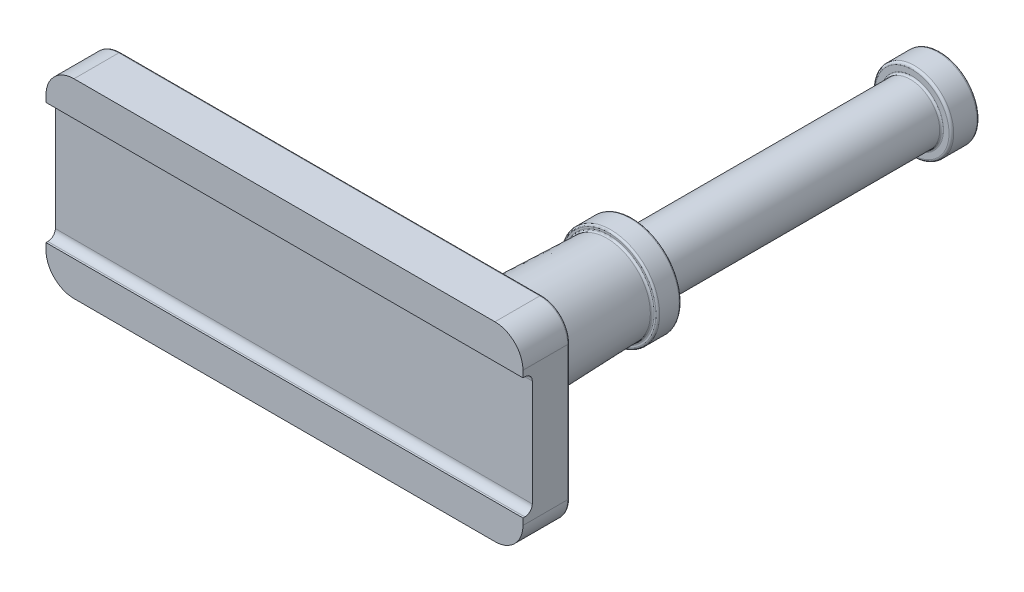
SolidWorks part; units mm, degrees
ref_plane "前视基准面" through (0, 0, 0) normal (0, 0, 1) x (1, 0, 0)
ref_plane "上视基准面" through (0, 0, 0) normal (0, 1, 0) x (1, 0, 0)
ref_plane "右视基准面" through (0, 0, 0) normal (1, 0, 0) x (0, 0, -1)
sketch "Sketch1" plane through (0, 0, 0) normal (0, 0, 1) x (1, 0, 0)
  line L1 (-1277.5, -510) -> (1277.5, -510)
  line L2 (-1277.5, -510) -> (-1277.5, 510)
  line L3 (-1277.5, 510) -> (1277.5, 510)
  line L4 (1277.5, -510) -> (1277.5, 510)
  line L5 (-1277.5, -510) -> (1277.5, 510) construction
  line L6 (-1277.5, 510) -> (1277.5, -510) construction
  point P0 (0, 0)
  dimension "D1" = 2555
  dimension "D2" = 1020
extrude "Extrude1" add sketch "Sketch1" along normal blind 250
fillet "Fillet1" radius 150 4 edges at (1277.5, -510, 125) (-1277.5, -510, 125) (1277.5, 510, 125) (-1277.5, 510, 125)
ref_plane "Plane1" through (762.5, 0, 0) normal (1, 0, 0) x (0, 0, -1)
sketch "Sketch4" plane through (762.5, 0, 0) normal (1, 0, 0) x (0, 0, -1)
  line L0 (0, 0) -> (2500, 0)
  line L1 (0, -360) -> (0, 360) construction
  line L2 (2500, 0) -> (2500, 210)
  line L3 (2500, 210) -> (2350, 210)
  line L4 (2350, 210) -> (2350, 157.5)
  line L5 (2350, 157.5) -> (850, 157.5)
  line L6 (850, 157.5) -> (850, 262.5)
  line L7 (850, 262.5) -> (725, 262.5)
  line L8 (725, 262.5) -> (725, 232.5)
  line L9 (725, 232.5) -> (80, 255.0239)
  line L10 (80, 255.0239) -> (80, 300)
  line L11 (80, 300) -> (0, 300)
  line L12 (0, 300) -> (0, 0)
  line L13 (2500, 0) -> (2810.0618, 0) construction
  dimension "D1" = 2500
  dimension "D2" = 150
  dimension "D3" = 1500
  dimension "D4" = 420
  dimension "D5" = 315
  dimension "D6" = 525
  dimension "D7" = 125
  dimension "D8" = 2
  dimension "D9" = 80
  dimension "D10" = 600
  dimension "D11" = 30
revolve "Revolve1" add sketch "Sketch4" angle 360 about L13
fillet "Fillet2" radius 10 8 edges at (920, 0, -2350) (920, 0, -850) (995, 0, -725) (1025, 0, -725) (1025, 0, -850) (1017.5239, 0, -80) (1062.5, 0, -80) (1062.5, 0, 0)
sketch "Sketch5" plane through (0, 0, 0) normal (0, 0, -1) x (-1, 0, 0)
  line L1 (1127.5, 395) -> (1127.5, 315)
  line L2 (1127.5, 315) -> (1072.5, 260)
  line L3 (1072.5, 260) -> (-290, 260)
  line L4 (-290, 260) -> (-302.5, 272.5)
  line L5 (-302.5, 272.5) -> (-382.5, 272.5)
  line L6 (-382.5, 272.5) -> (-382.5, 222.5)
  line L7 (-382.5, 222.5) -> (-302.5, 222.5)
  line L8 (-302.5, 222.5) -> (-290, 235)
  line L9 (-427.5, 420) -> (-427.5, -420) construction
  line L10 (-1277.5, -360) -> (-1277.5, 360) construction
  line L11 (-290, 235) -> (1072.5, 235)
  line L12 (1127.5, -420) -> (-1127.5, -420)
  line L13 (1187.5, 360) -> (1187.5, -360)
  line L14 (-1127.5, 420) -> (1127.5, 420)
  line L15 (1127.5, -420) -> (-382.5, -420)
  line L16 (1187.5, 360) -> (1187.5, -360)
  line L17 (-382.5, 420) -> (1127.5, 420)
  line L18 (1072.5, 235) -> (1072.5, 95)
  line L19 (1072.5, 95) -> (-290, 95)
  line L20 (-290, 95) -> (-302.5, 107.5)
  line L21 (-302.5, 107.5) -> (-382.5, 107.5)
  line L22 (-382.5, 107.5) -> (-382.5, 57.5)
  line L23 (-382.5, 57.5) -> (-302.5, 57.5)
  line L24 (-302.5, 57.5) -> (-290, 70)
  line L25 (-290, 70) -> (1072.5, 70)
  line L26 (1072.5, 70) -> (1072.5, -70)
  line L27 (1072.5, -70) -> (-290, -70)
  line L28 (-290, -70) -> (-302.5, -57.5)
  line L29 (-302.5, -57.5) -> (-382.5, -57.5)
  line L30 (-382.5, -57.5) -> (-382.5, -107.5)
  line L31 (-382.5, -107.5) -> (-302.5, -107.5)
  line L32 (-302.5, -107.5) -> (-290, -95)
  line L33 (-290, -95) -> (1072.5, -95)
  line L34 (1072.5, -95) -> (1072.5, -235)
  line L35 (1072.5, -235) -> (-290, -235)
  line L36 (-290, -235) -> (-302.5, -222.5)
  line L37 (-302.5, -222.5) -> (-382.5, -222.5)
  line L38 (-382.5, -222.5) -> (-382.5, -272.5)
  line L39 (-382.5, -272.5) -> (-302.5, -272.5)
  line L40 (-302.5, -272.5) -> (-290, -260)
  line L41 (-290, -260) -> (1072.5, -260)
  line L42 (1072.5, -260) -> (1127.5, -315)
  line L43 (1127.5, -315) -> (1127.5, -395)
  line L45 (1127.5, 395) -> (-292.3612, 395)
  line L46 (-292.3612, -395) -> (1127.5, -395)
  arc A0 (-339.8027, -360.7895) -> (-382.5, -420) centre (-382.5, -375) ccw
  arc A1 (-339.8027, -360.7895) -> (-292.3612, -395) centre (-292.3612, -345) ccw
  arc A2 (-292.3612, 395) -> (-339.8027, 360.7895) centre (-292.3612, 345) ccw
  arc A6 (-382.5, 420) -> (-339.8027, 360.7895) centre (-382.5, 375) ccw
  arc A8 (1127.5, -420) -> (1187.5, -360) centre (1127.5, -360) ccw
  arc A9 (1187.5, 360) -> (1127.5, 420) centre (1127.5, 360) ccw
  arc A10 (1127.5, -420) -> (1187.5, -360) centre (1127.5, -360) ccw
  arc A11 (1187.5, 360) -> (1127.5, 420) centre (1127.5, 360) ccw
  dimension "D3" = 90
  dimension "D19" = 100
  dimension "D20" = 100
  dimension "D2" = 850
  dimension "D4" = 45
  dimension "D5" = 45
  dimension "D6" = 45
  dimension "D7" = 45
  dimension "D8" = 45
  dimension "D9" = 45
  dimension "D10" = 45
  dimension "D11" = 45
  dimension "D12" = 45
  dimension "D13" = 45
  dimension "D14" = 25
  dimension "D15" = 45
  dimension "D16" = 25
  dimension "D17" = 50
  dimension "D18" = 80
  dimension "D21" = 25
  dimension "D22" = 140
  dimension "D1" = 90
extrude "Extrude2" cut sketch "Sketch5" against normal blind 150
fillet "Fillet3" radius 20 12 edges at (-1127.5, 315, 75) (-1072.5, 260, 75) (-1072.5, 235, 75) (-1072.5, 95, 75) (-1072.5, 70, 75) (-1072.5, -70, 75) (-1072.5, -95, 75) (-1072.5, -235, 75) (-1072.5, -260, 75) (-1127.5, -315, 75) (-1127.5, 395, 75) (-1127.5, -395, 75)
sketch "Sketch7" plane through (0, 0, 0) normal (0, 0, -1) x (-1, 0, 0)
  line L0 (-557.5, -420) -> (-1127.5, -420)
  line L1 (-1187.5, -360) -> (-1187.5, 360)
  line L2 (-1127.5, 420) -> (-557.5, 420)
  line L3 (-517.5, 380) -> (-517.5, 337.6389)
  line L4 (-517.5, -380) -> (-517.5, -337.6389)
  line L5 (-1277.5, -360) -> (-1277.5, 360) construction
  line L6 (1127.5, -510) -> (-1127.5, -510) construction
  line L7 (-1127.5, 510) -> (1127.5, 510) construction
  arc A0 (-1127.5, -420) -> (-1187.5, -360) centre (-1127.5, -360) cw
  arc A1 (-1187.5, 360) -> (-1127.5, 420) centre (-1127.5, 360) cw
  arc A2 (-578.2595, 303.4476) -> (-578.2595, -303.4476) centre (-762.5, 0) ccw
  arc A6 (-339.8027, -360.7895) -> (-382.5, -420) centre (-382.5, -375) ccw construction
  circle A8 centre (-762.5, 0) radius 310 construction
  arc A9 (-517.5, -337.6389) -> (-578.2595, -303.4476) centre (-557.5, -337.6389) ccw
  arc A10 (-382.5, 420) -> (-339.8027, 360.7895) centre (-382.5, 375) ccw construction
  arc A11 (-557.5, -420) -> (-517.5, -380) centre (-557.5, -380) ccw
  arc A12 (-557.5, 420) -> (-517.5, 380) centre (-557.5, 380) cw
  arc A13 (-517.5, 337.6389) -> (-578.2595, 303.4476) centre (-557.5, 337.6389) cw
  dimension "D6" = 60
  dimension "D7" = 60
  dimension "D8" = 45
  dimension "D9" = 40
  dimension "D1" = 90
  dimension "D2" = 90
  dimension "D3" = 90
  dimension "D4" = 90
  dimension "D5" = 90
extrude "Extrude3" cut sketch "Sketch7" against normal blind 50
fillet "Fillet4" radius 10 90 edges at (-1125.9776, 315.6306, 0) (-1100, 287.5, 0) (-1071.8694, 261.5224, 0) (-387.1079, 260, 0) (296.25, 266.25, 0) (342.5, 272.5, 0) (382.5, 247.5, 0) (342.5, 222.5, 0) (296.25, 228.75, 0) (-381.25, 235, 0) (-1066.6421, 229.1421, 0) (-1072.5, 165, 0) (-1066.6421, 100.8579, 0) (-381.25, 95, 0) (296.25, 101.25, 0) (342.5, 107.5, 0) (382.5, 82.5, 0) (342.5, 57.5, 0) (296.25, 63.75, 0) (-381.25, 70, 0) (-1066.6421, 64.1421, 0) (-1072.5, 0, 0) (-1066.6421, -64.1421, 0) (-381.25, -70, 0) (296.25, -63.75, 0) (342.5, -57.5, 0) (382.5, -82.5, 0) (342.5, -107.5, 0) (296.25, -101.25, 0) (-381.25, -95, 0) (-1066.6421, -100.8579, 0) (-1072.5, -165, 0) (-1066.6421, -229.1421, 0) (-381.25, -235, 0) (296.25, -228.75, 0) (342.5, -222.5, 0) (382.5, -247.5, 0) (342.5, -272.5, 0) (296.25, -266.25, 0) (-387.1079, -260, 0) (-1071.8694, -261.5224, 0) (-1100, -287.5, 0) (-1125.9776, -315.6306, 0) (-1127.5, -349.1421, 0) (-1121.6421, -389.1421, 0) (-407.5694, -395, 0) (321.6061, -385.5554, 0) (418.9998, -348.6796, 0) (-372.5, -420, 0) (-1169.9264, -402.4264, 0) (-1187.5, 0, 0) (-1169.9264, 402.4264, 0) (-372.5, 420, 0) (418.9998, 348.6796, 0) (321.6061, 385.5554, 0) (-407.5694, 395, 0) (-1121.6421, 389.1421, 0) (-1127.5, 349.1421, 0) (1233.566, 466.066, 0) (0, 510, 0) (-1233.566, 466.066, 0) (-1277.5, 0, 0) (-1233.566, -466.066, 0) (0, -510, 0) (1233.566, -466.066, 0) (1277.5, 0, 0) (842.5, -420, 0) (529.2157, -408.2843, 0) (517.5, -358.8194, 0) (537.8834, -302.7793, 0) (1117.5, 0, 0) (537.8834, 302.7793, 0) (517.5, 358.8194, 0) (529.2157, 408.2843, 0) (842.5, 420, 0) (1169.9264, 402.4264, 0) (1187.5, 0, 0) (1169.9264, -402.4264, 0) (1187.5, 0, 50) (1169.9264, 402.4264, 50) (842.5, 420, 50) (529.2157, 408.2843, 50) (517.5, 358.8194, 50) (537.8834, 302.7793, 50) (1117.5, 0, 50) (537.8834, -302.7793, 50) (517.5, -358.8194, 50) (529.2157, -408.2843, 50) (842.5, -420, 50) (1169.9264, -402.4264, 50)
sketch "Sketch8" plane through (1277.5, 0, 0) normal (1, 0, 0) x (0, 0, -1)
  line L0 (0, 0) -> (-355.8382, 0) construction
  line L1 (0, 360) -> (0, -360) construction
  line L2 (-250, 325) -> (-240, 325)
  line L3 (-250, -360) -> (-250, 360) construction
  line L4 (-200, 285) -> (-200, -285)
  line L5 (-240, -325) -> (-250, -325)
  line L6 (-250, -325) -> (-250, 325)
  arc A0 (-240, 325) -> (-200, 285) centre (-240, 285) cw
  arc A1 (-200, -285) -> (-240, -325) centre (-240, -285) cw
  dimension "D3" = 40
  dimension "D4" = 40
  dimension "D1" = 650
  dimension "D2" = 50
extrude "Extrude4" cut sketch "Sketch8" against normal through all
scale "Scale1" bodies to scale 110 scale about centroid uniform scaling yes scale factor 0.8
fillet "Fillet5" radius 10 2 edges at (839.3404, 0, -1941.0003) (839.3404, 0, -2061.0003)
sketch "Sketch10" plane through (0, 0, 138.9997) normal (0, 0, 1) x (1, 0, 0)
  point P0 (671.3404, 0)
